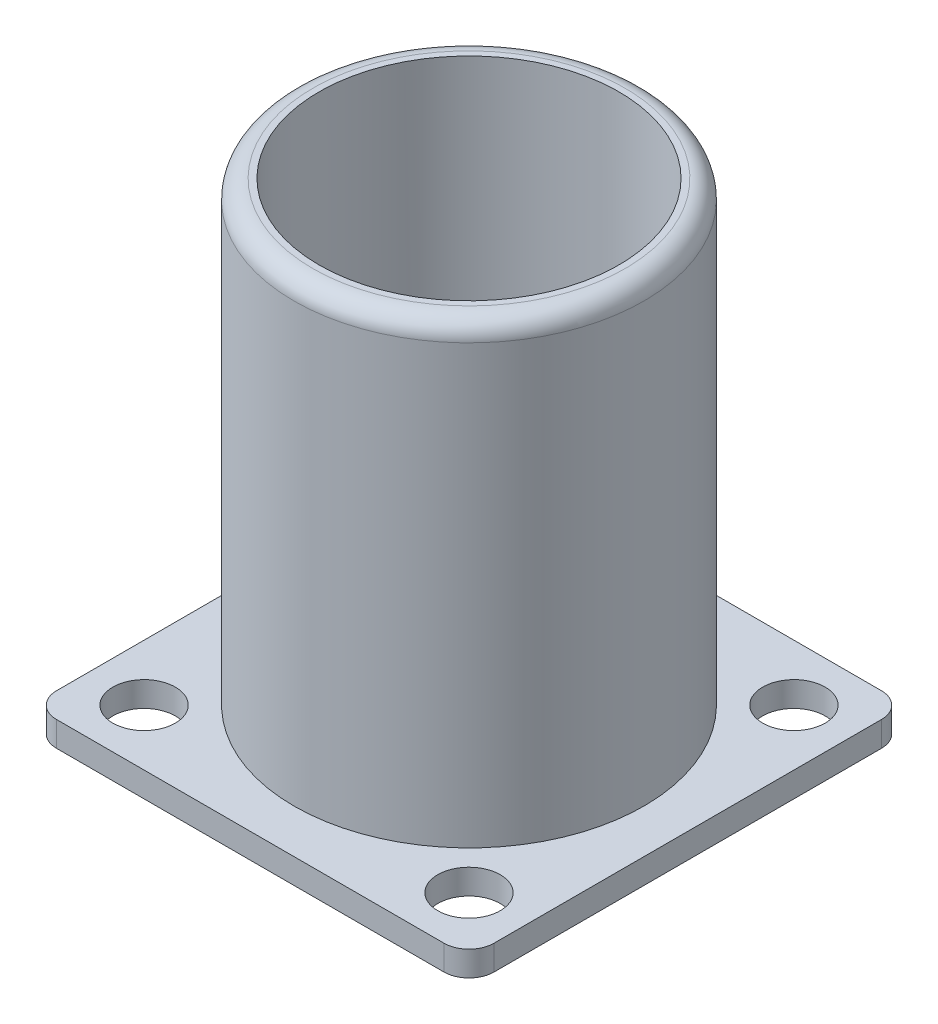
SolidWorks part; units mm, degrees
ref_plane "Plano frontal" through (0, 0, 0) normal (0, 0, 1) x (1, 0, 0)
ref_plane "Plano superior" through (0, 0, 0) normal (0, 1, 0) x (1, 0, 0)
ref_plane "Plano direito" through (0, 0, 0) normal (1, 0, 0) x (0, 0, -1)
sketch "Esboço1" plane through (0, 0, 0) normal (0, 1, 0) x (1, 0, 0)
  line L0 (0, 0) -> (17.5, 0) construction
  line L1 (-17.5, -17.5) -> (17.5, -17.5)
  line L2 (-17.5, -17.5) -> (-17.5, 17.5)
  line L3 (-17.5, 17.5) -> (17.5, 17.5)
  line L4 (17.5, -17.5) -> (17.5, 17.5)
  line L5 (-17.5, -17.5) -> (17.5, 17.5) construction
  line L6 (-17.5, 17.5) -> (17.5, -17.5) construction
  line L7 (-17.5, -13) -> (-13, -13) construction
  line L8 (-17.5, -13) -> (-17.5, -17.5) construction
  line L9 (-17.5, -17.5) -> (-13, -17.5) construction
  line L10 (-13, -13) -> (-13, -17.5) construction
  line L11 (-17.5, -13) -> (-13, -17.5) construction
  line L12 (-17.5, -17.5) -> (-13, -13) construction
  line L13 (0, 0) -> (0, -17.5) construction
  line L14 (0, 0) -> (0, 17.5) construction
  line L15 (-0.75, -11.9765) -> (-0.75, 12)
  line L16 (-12, -12) -> (-10.7087, -12) construction
  line L17 (-12, -12) -> (-12, 12) construction
  line L18 (-12, 12) -> (-0.75, 12) construction
  line L19 (12, -12) -> (12, 12) construction
  line L20 (-12, -12) -> (12, 12) construction
  line L21 (-12, 12) -> (12, -12) construction
  line L22 (0.75, -11.9765) -> (0.75, 12)
  line L23 (0.75, 0) -> (0.75, 17.5) construction
  line L24 (-0.75, 0) -> (-0.75, 17.5) construction
  line L25 (0.75, 12) -> (0.75, 17.5) construction
  line L26 (-0.75, 12) -> (-0.75, 17.5) construction
  line L27 (0.75, -11.9765) -> (0.75, 12)
  line L28 (2.25, -11.9765) -> (2.25, 12)
  line L29 (2.25, -11.9765) -> (2.25, 12)
  line L30 (3.75, -11.9765) -> (3.75, 12)
  line L31 (3.75, -11.9765) -> (3.75, 12)
  line L32 (5.25, -11.9765) -> (5.25, 12)
  line L33 (5.25, -11.9765) -> (5.25, 12)
  line L34 (6.75, -11.9765) -> (6.75, 12)
  line L35 (6.75, -11.9765) -> (6.75, 12)
  line L36 (8.25, -11.9765) -> (8.25, 12)
  line L37 (8.25, -11.9765) -> (8.25, 12)
  line L38 (9.75, -11.9765) -> (9.75, 12)
  line L39 (9.75, -11.9765) -> (9.75, 12)
  line L40 (11.25, -11.9765) -> (11.25, 12)
  line L41 (0, -11.9765) -> (0.75, -11.9765) construction
  line L42 (0, 12) -> (0.75, 12) construction
  line L43 (0.75, 12) -> (12, 12) construction
  line L44 (-0.75, 12) -> (0, 12) construction
  line L45 (-10.7087, -12) -> (0, -12) construction
  line L46 (0, -12) -> (12, -12) construction
  line L47 (-0.75, -11.9765) -> (0, -11.9765) construction
  line L48 (-11.25, -11.9765) -> (-11.25, 12)
  line L49 (-9.75, -11.9765) -> (-9.75, 12)
  line L50 (-8.25, -11.9765) -> (-8.25, 12)
  line L51 (-6.75, -11.9765) -> (-6.75, 12)
  line L52 (-5.25, -11.9765) -> (-5.25, 12)
  line L53 (-3.75, -11.9765) -> (-3.75, 12)
  line L54 (-2.25, -11.9765) -> (-2.25, 12)
  circle A0 centre (-13, -13) radius 2.5
  circle A1 centre (13, -13) radius 2.5
  circle A2 centre (13, 13) radius 2.5
  circle A3 centre (-13, 13) radius 2.5
  arc A4 (-0.75, 11.9765) -> (-2.25, 11.7872) centre (0, 0) ccw
  arc A5 (0.75, 11.9765) -> (0, 12) centre (0, 0) ccw construction
  arc A6 (0, 12) -> (-0.75, 11.9765) centre (0, 0) ccw construction
  arc A7 (-0.75, -11.9765) -> (0, -12) centre (0, 0) ccw construction
  arc A8 (0, -12) -> (2.25, -11.7872) centre (0, 0) ccw
  arc A9 (2.25, -11.7872) -> (3.75, -11.399) centre (0, 0) ccw construction
  arc A10 (3.75, -11.399) -> (5.25, -10.7906) centre (0, 0) ccw
  arc A11 (3.75, 11.399) -> (2.25, 11.7872) centre (0, 0) ccw construction
  arc A12 (2.25, 11.7872) -> (0.75, 11.9765) centre (0, 0) ccw
  arc A13 (6.75, 9.9216) -> (5.25, 10.7906) centre (0, 0) ccw construction
  arc A14 (5.25, 10.7906) -> (3.75, 11.399) centre (0, 0) ccw
  arc A15 (5.25, -10.7906) -> (6.75, -9.9216) centre (0, 0) ccw construction
  arc A16 (6.75, -9.9216) -> (8.4853, -8.4853) centre (0, 0) ccw
  arc A17 (9.75, 6.9955) -> (8.4853, 8.4853) centre (0, 0) ccw construction
  arc A18 (8.4853, 8.4853) -> (6.75, 9.9216) centre (0, 0) ccw
  arc A19 (8.4853, -8.4853) -> (9.75, -6.9955) centre (0, 0) ccw construction
  arc A20 (9.75, -6.9955) -> (11.25, -4.1758) centre (0, 0) ccw
  arc A21 (12, 0) -> (11.25, 4.1758) centre (0, 0) ccw construction
  arc A22 (11.25, 4.1758) -> (9.75, 6.9955) centre (0, 0) ccw
  arc A23 (11.25, -4.1758) -> (12, 0) centre (0, 0) ccw construction
  arc A24 (-2.25, 11.7872) -> (-3.75, 11.399) centre (0, 0) ccw construction
  arc A25 (-3.75, 11.399) -> (-5.25, 10.7906) centre (0, 0) ccw
  arc A26 (-3.75, -11.399) -> (-2.25, -11.7872) centre (0, 0) ccw construction
  arc A27 (-2.25, -11.7872) -> (-0.75, -11.9765) centre (0, 0) ccw
  arc A28 (-6.75, -9.9216) -> (-5.25, -10.7906) centre (0, 0) ccw construction
  arc A29 (-5.25, -10.7906) -> (-3.75, -11.399) centre (0, 0) ccw
  arc A30 (-5.25, 10.7906) -> (-6.75, 9.9216) centre (0, 0) ccw construction
  arc A31 (-6.75, 9.9216) -> (-8.4853, 8.4853) centre (0, 0) ccw
  arc A32 (-8.4853, 8.4853) -> (-9.75, 6.9955) centre (0, 0) ccw construction
  arc A33 (-9.75, 6.9955) -> (-11.25, 4.1758) centre (0, 0) ccw
  arc A34 (-9.75, -6.9955) -> (-8.4853, -8.4853) centre (0, 0) ccw construction
  arc A35 (-8.4853, -8.4853) -> (-6.75, -9.9216) centre (0, 0) ccw
  arc A36 (-12, 0) -> (-11.25, -4.1758) centre (0, 0) ccw construction
  arc A37 (-11.25, -4.1758) -> (-9.75, -6.9955) centre (0, 0) ccw
  arc A38 (-11.25, 4.1758) -> (-12, 0) centre (0, 0) ccw construction
  point P0 (0, 0)
  point P6 (-15.25, -15.25)
  dimension "D3" = 5
  dimension "D4" = 24
  dimension "D1" = 35
  dimension "D2" = 4.5
  dimension "D8" = 1.5
  dimension "D5" = 0.75
  dimension "D6" = 0.75
  dimension "D7" = 8
extrude "Ressalto-extrusão1" add sketch "Esboço1" along normal blind 2
ref_plane "Plano1" through (0, 2, 0) normal (0, 1, 0) x (1, 0, 0)
fillet "Filete2" radius 2 4 edges at (-17.5, 1, 17.5) (17.5, 1, 17.5) (17.5, 1, -17.5) (-17.5, 1, -17.5)
sketch "Esboço3" plane through (0, 2, 0) normal (0, 1, 0) x (1, 0, 0)
  circle A0 centre (0, 0) radius 12
  arc A1 (-0.75, 11.9765) -> (-2.25, 11.7872) centre (0, 0) ccw construction
  circle A2 centre (0, 0) radius 14
  dimension "D1" = 2
extrude "Ressalto-extrusão3" add sketch "Esboço3" along normal blind 36.5
fillet "Filete3" radius 1.5 1 edges at (0, 38.5, 14)
equation "\"D6@Esboço1\"=\"D5@Esboço1\""
